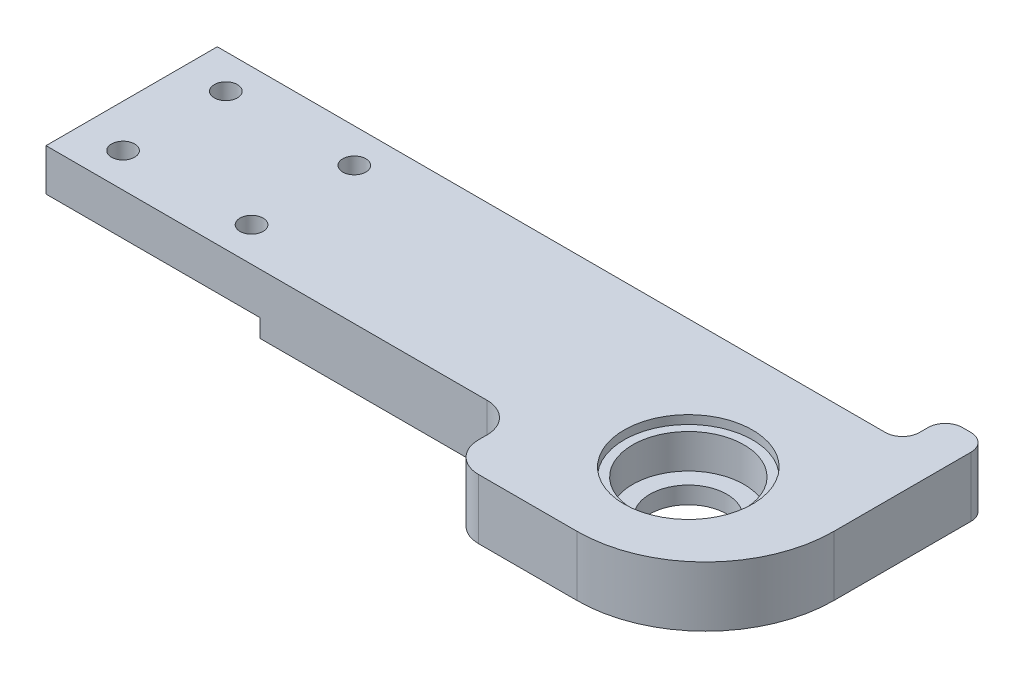
SolidWorks part; units mm, degrees
ref_plane "Front Plane" through (0, 0, 0) normal (0, 0, 1) x (1, 0, 0)
ref_plane "Top Plane" through (0, 0, 0) normal (0, 1, 0) x (1, 0, 0)
ref_plane "Right Plane" through (0, 0, 0) normal (1, 0, 0) x (0, 0, -1)
sketch "Sketch1" plane through (0, 0, 0) normal (0, 1, 0) x (1, 0, 0)
  line L0 (85, 0) -> (85, 5) construction
  line L1 (0, 0) -> (55, 0)
  line L2 (0, 0) -> (0, 20)
  line L3 (0, 20) -> (85, 20)
  line L4 (85, 0) -> (85, 20)
  line L5 (85, 5) -> (70, 5) construction
  line L8 (85, 0) -> (85, -8)
  line L9 (85, -8) -> (55, -8)
  line L10 (55, 0) -> (55, -8)
  circle A0 centre (70, 5) radius 4.5
  dimension "D4" = 9
  dimension "D1" = 20
  dimension "D2" = 85
  dimension "D3" = 5
  dimension "D5" = 15
  dimension "D6" = 30
  dimension "D7" = 8
extrude "Boss-Extrude1" add sketch "Sketch1" along normal blind 7
sketch "Sketch2" plane through (0, 0, 0) normal (0, -1, 0) x (1, 0, 0)
  line L0 (85, -20) -> (0, -20) construction
  line L1 (0, 0) -> (25, 0)
  line L2 (0, 0) -> (0, -20)
  line L3 (0, -20) -> (25, -20)
  line L4 (25, 0) -> (25, -20)
  dimension "D1" = 25
extrude "Cut-Extrude1" cut sketch "Sketch2" against normal blind 2.1
sketch "Sketch3" plane through (0, 2.1, 0) normal (0, -1, 0) x (1, 0, 0)
  line L0 (0, -10) -> (25, -10) construction
  line L1 (0, 0) -> (0, -20) construction
  line L2 (25, -20) -> (25, 0) construction
  line L4 (5, -16) -> (20, -16) construction
  line L5 (5, -16) -> (5, -4) construction
  line L6 (5, -4) -> (20, -4) construction
  line L7 (20, -16) -> (20, -4) construction
  line L8 (5, -16) -> (20, -4) construction
  line L9 (5, -4) -> (20, -16) construction
  circle A0 centre (5, -4) radius 1.35
  circle A1 centre (20, -4) radius 1.35
  circle A2 centre (20, -16) radius 1.35
  circle A3 centre (5, -16) radius 1.35
  point P6 (12.5, -10)
  dimension "D1" = 15
  dimension "D2" = 12
extrude "Cut-Extrude2" cut sketch "Sketch3" against normal blind 14
fillet "Fillet2" radius 3.5 2 edges at (55, 3.5, 8) (55, 3.5, 0)
sketch "Sketch4" plane through (0, 7, 0) normal (0, 1, 0) x (1, 0, 0)
  circle A0 centre (70, 5) radius 7.5
  dimension "D1" = 15
extrude "Cut-Extrude3" cut sketch "Sketch4" against normal blind 1
sketch "Sketch5" plane through (0, 6, 0) normal (0, 1, 0) x (1, 0, 0)
  circle A0 centre (70, 5) radius 6.5
  dimension "D1" = 13
extrude "Cut-Extrude4" cut sketch "Sketch5" against normal blind 4
fillet "Fillet3" radius 15 1 edges at (85, 3.5, 8)
sketch "Sketch6" plane through (0, 7, 0) normal (0, 1, 0) x (1, 0, 0)
  line L1 (85, 20) -> (80, 20)
  line L2 (85, 20) -> (85, 25)
  line L3 (85, 25) -> (80, 25)
  line L4 (80, 20) -> (80, 25)
  dimension "D1" = 5
  dimension "D2" = 5
extrude "Boss-Extrude2" add sketch "Sketch6" against normal up to surface (7 mm away) up to face at (57.0118, 0, -2.2104)
fillet "Fillet4" radius 2 3 edges at (85, 3.5, -25) (80, 3.5, -25) (80, 3.5, -20)
